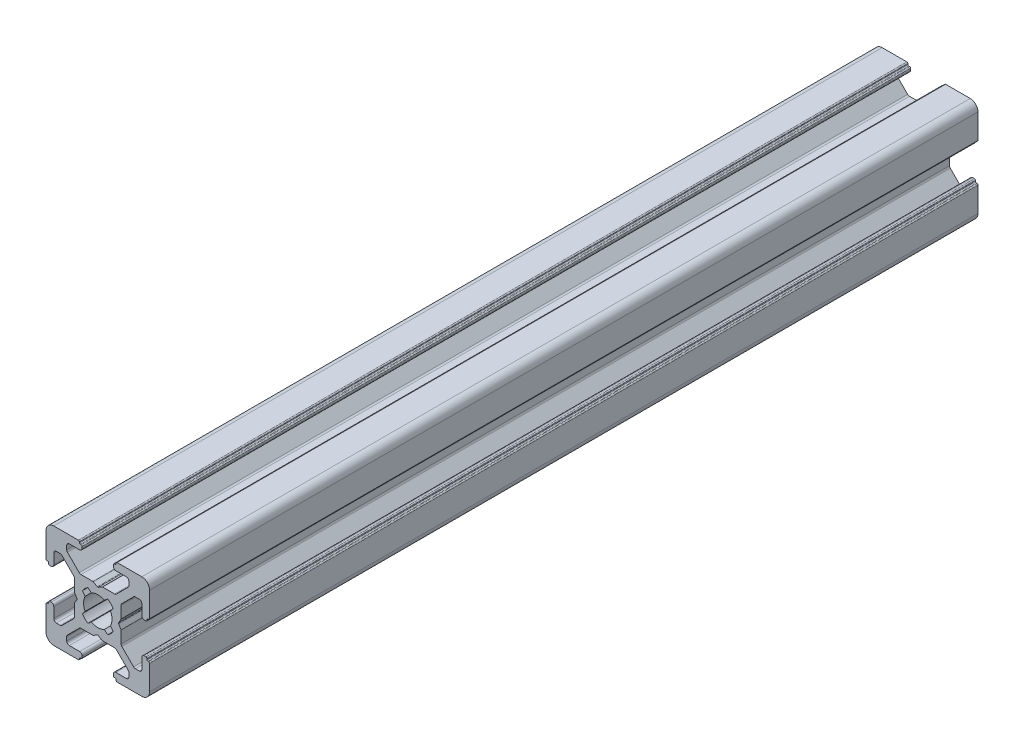
SolidWorks part; units mm, degrees
ref_plane "Front Plane" through (0, 0, 0) normal (0, 0, 1) x (1, 0, 0)
ref_plane "Top Plane" through (0, 0, 0) normal (0, 1, 0) x (1, 0, 0)
ref_plane "Right Plane" through (0, 0, 0) normal (1, 0, 0) x (0, 0, -1)
sketch "Sketch1" plane through (0, 0, 0) normal (0, 0, 1) x (1, 0, 0)
  line L0 (0, 13.3675) -> (0, -10.9159) construction
  line L1 (-12.9725, 0) -> (15.1887, 0) construction
  line L2 (-3.5, 8.5) -> (-5.5, 8.5)
  line L3 (-3.55, 9.7) -> (-3.55, 9.8)
  line L4 (-6, 7.2678) -> (-6, 8)
  line L5 (-7.2678, 6) -> (-8, 6)
  line L6 (-3.75, 10) -> (-8.5, 10)
  line L7 (-9.7, 3.55) -> (-9.8, 3.55)
  line L8 (-9.5, 3.2) -> (-9.5, 3.35)
  line L9 (-9, 3) -> (-9.3, 3)
  line L10 (-4.4732, 0.8536) -> (-4.0381, 0.1)
  line L11 (-4.5, 3.2322) -> (-4.5, 0.9536)
  line L12 (-8.5, 3.5) -> (-8.5, 5.5)
  line L13 (-10, 3.75) -> (-10, 8.5)
  line L14 (-3.5858, 4.6464) -> (-5.8536, 6.9142)
  line L15 (-4.6464, 3.5858) -> (-6.9142, 5.8536)
  line L16 (-3.2, 9.5) -> (-3.35, 9.5)
  line L17 (-3, 9) -> (-3, 9.3)
  line L18 (-0.8536, 4.4732) -> (-0.1, 4.0381)
  line L19 (-3.2322, 4.5) -> (-0.9536, 4.5)
  line L20 (-1.2582, 2.4453) -> (-1.9139, 2.9896)
  line L21 (-2.4453, 1.2582) -> (-2.9922, 1.9099)
  line L22 (3.5, -8.5) -> (5.5, -8.5)
  line L23 (3.55, -9.7) -> (3.55, -9.8)
  line L24 (6, -7.2678) -> (6, -8)
  line L25 (7.2678, -6) -> (8, -6)
  line L26 (3.75, -10) -> (8.5, -10)
  line L27 (9.7, -3.55) -> (9.8, -3.55)
  line L28 (9.5, -3.2) -> (9.5, -3.35)
  line L29 (9, -3) -> (9.3, -3)
  line L30 (4.4732, -0.8536) -> (4.0381, -0.1)
  line L31 (4.5, -3.2322) -> (4.5, -0.9536)
  line L32 (8.5, -3.5) -> (8.5, -5.5)
  line L33 (10, -3.75) -> (10, -8.5)
  line L34 (3.5858, -4.6464) -> (5.8536, -6.9142)
  line L35 (4.6464, -3.5858) -> (6.9142, -5.8536)
  line L36 (3.2, -9.5) -> (3.35, -9.5)
  line L37 (3, -9) -> (3, -9.3)
  line L38 (0.8536, -4.4732) -> (0.1, -4.0381)
  line L39 (3.2322, -4.5) -> (0.9536, -4.5)
  line L40 (1.2582, -2.4453) -> (1.9139, -2.9896)
  line L41 (2.4453, -1.2582) -> (2.9922, -1.9099)
  line L42 (-2.4453, -1.2582) -> (-2.9922, -1.9099)
  line L43 (-1.2582, -2.4453) -> (-1.9139, -2.9896)
  line L44 (-3.2322, -4.5) -> (-0.9536, -4.5)
  line L45 (-0.8536, -4.4732) -> (-0.1, -4.0381)
  line L46 (-3, -9) -> (-3, -9.3)
  line L47 (-3.2, -9.5) -> (-3.35, -9.5)
  line L48 (-4.6464, -3.5858) -> (-6.9142, -5.8536)
  line L49 (-3.5858, -4.6464) -> (-5.8536, -6.9142)
  line L50 (-10, -3.75) -> (-10, -8.5)
  line L51 (-8.5, -3.5) -> (-8.5, -5.5)
  line L52 (-4.5, -3.2322) -> (-4.5, -0.9536)
  line L53 (-4.4732, -0.8536) -> (-4.0381, -0.1)
  line L54 (-9, -3) -> (-9.3, -3)
  line L55 (-9.5, -3.2) -> (-9.5, -3.35)
  line L56 (-9.7, -3.55) -> (-9.8, -3.55)
  line L57 (2.4453, 1.2582) -> (2.9922, 1.9099)
  line L58 (1.2582, 2.4453) -> (1.9139, 2.9896)
  line L59 (3.2322, 4.5) -> (0.9536, 4.5)
  line L60 (0.8536, 4.4732) -> (0.1, 4.0381)
  line L61 (-3.75, -10) -> (-8.5, -10)
  line L62 (-7.2678, -6) -> (-8, -6)
  line L63 (-6, -7.2678) -> (-6, -8)
  line L64 (3, 9) -> (3, 9.3)
  line L65 (3.2, 9.5) -> (3.35, 9.5)
  line L66 (4.6464, 3.5858) -> (6.9142, 5.8536)
  line L67 (3.5858, 4.6464) -> (5.8536, 6.9142)
  line L68 (10, 3.75) -> (10, 8.5)
  line L69 (8.5, 3.5) -> (8.5, 5.5)
  line L70 (4.5, 3.2322) -> (4.5, 0.9536)
  line L71 (4.4732, 0.8536) -> (4.0381, 0.1)
  line L72 (9, 3) -> (9.3, 3)
  line L73 (9.5, 3.2) -> (9.5, 3.35)
  line L74 (9.7, 3.55) -> (9.8, 3.55)
  line L75 (3.75, 10) -> (8.5, 10)
  line L76 (7.2678, 6) -> (8, 6)
  line L77 (6, 7.2678) -> (6, 8)
  line L78 (3.55, 9.7) -> (3.55, 9.8)
  line L79 (3.5, 8.5) -> (5.5, 8.5)
  line L80 (-3.55, -9.7) -> (-3.55, -9.8)
  line L81 (-3.5, -8.5) -> (-5.5, -8.5)
  arc A0 (-10, 8.5) -> (-8.5, 10) centre (-8.5, 8.5) cw
  arc A1 (-8.5, 5.5) -> (-8, 6) centre (-8, 5.5) cw
  arc A2 (-7.2678, 6) -> (-6.9142, 5.8536) centre (-7.2678, 5.5) cw
  arc A3 (-5.8536, 6.9142) -> (-6, 7.2678) centre (-5.5, 7.2678) cw
  arc A4 (-6, 8) -> (-5.5, 8.5) centre (-5.5, 8) cw
  arc A5 (-9.7, 3.55) -> (-9.5, 3.35) centre (-9.7, 3.35) cw
  arc A6 (-9.8, 3.55) -> (-10, 3.75) centre (-9.8, 3.75) cw
  arc A7 (-9.3, 3) -> (-9.5, 3.2) centre (-9.3, 3.2) cw
  arc A8 (-8.5, 3.5) -> (-9, 3) centre (-9, 3.5) cw
  arc A9 (-4.6464, 3.5858) -> (-4.5, 3.2322) centre (-5, 3.2322) cw
  arc A10 (-4.4732, 0.8536) -> (-4.5, 0.9536) centre (-4.3, 0.9536) cw
  arc A11 (-4.0381, 0.1) -> (-4.0381, -0.1) centre (-4.2113, 0) cw
  arc A12 (-3.2, 9.5) -> (-3, 9.3) centre (-3.2, 9.3) cw
  arc A13 (-0.9536, 4.5) -> (-0.8536, 4.4732) centre (-0.9536, 4.3) cw
  arc A14 (-2.9922, 1.9099) -> (-1.9139, 2.9896) centre (0, 0) cw
  arc A15 (-3.2322, 4.5) -> (-3.5858, 4.6464) centre (-3.2322, 5) cw
  arc A16 (-3.75, 10) -> (-3.55, 9.8) centre (-3.75, 9.8) cw
  arc A17 (-3.35, 9.5) -> (-3.55, 9.7) centre (-3.35, 9.7) cw
  arc A18 (2.4453, -1.2582) -> (2.4453, 1.2582) centre (0, 0) ccw
  arc A19 (-3, 9) -> (-3.5, 8.5) centre (-3.5, 9) cw
  arc A20 (-2.4453, -1.2582) -> (-2.4453, 1.2582) centre (0, 0) cw
  arc A21 (10, -8.5) -> (8.5, -10) centre (8.5, -8.5) cw
  arc A22 (8.5, -5.5) -> (8, -6) centre (8, -5.5) cw
  arc A23 (7.2678, -6) -> (6.9142, -5.8536) centre (7.2678, -5.5) cw
  arc A24 (5.8536, -6.9142) -> (6, -7.2678) centre (5.5, -7.2678) cw
  arc A25 (6, -8) -> (5.5, -8.5) centre (5.5, -8) cw
  arc A26 (9.7, -3.55) -> (9.5, -3.35) centre (9.7, -3.35) cw
  arc A27 (9.8, -3.55) -> (10, -3.75) centre (9.8, -3.75) cw
  arc A28 (9.3, -3) -> (9.5, -3.2) centre (9.3, -3.2) cw
  arc A29 (8.5, -3.5) -> (9, -3) centre (9, -3.5) cw
  arc A30 (4.6464, -3.5858) -> (4.5, -3.2322) centre (5, -3.2322) cw
  arc A31 (4.4732, -0.8536) -> (4.5, -0.9536) centre (4.3, -0.9536) cw
  arc A32 (3.2, -9.5) -> (3, -9.3) centre (3.2, -9.3) cw
  arc A33 (-0.1, -4.0381) -> (0.1, -4.0381) centre (0, -4.2113) cw
  arc A34 (0.9536, -4.5) -> (0.8536, -4.4732) centre (0.9536, -4.3) cw
  arc A35 (2.9922, -1.9099) -> (1.9139, -2.9896) centre (0, 0) cw
  arc A36 (1.2582, -2.4453) -> (-1.2582, -2.4453) centre (0, 0) cw
  arc A37 (3.2322, -4.5) -> (3.5858, -4.6464) centre (3.2322, -5) cw
  arc A38 (3.75, -10) -> (3.55, -9.8) centre (3.75, -9.8) cw
  arc A39 (3.35, -9.5) -> (3.55, -9.7) centre (3.35, -9.7) cw
  arc A40 (3, -9) -> (3.5, -8.5) centre (3.5, -9) cw
  arc A41 (-3, -9) -> (-3.5, -8.5) centre (-3.5, -9) ccw
  arc A42 (-3.35, -9.5) -> (-3.55, -9.7) centre (-3.35, -9.7) ccw
  arc A43 (-3.75, -10) -> (-3.55, -9.8) centre (-3.75, -9.8) ccw
  arc A44 (-3.2322, -4.5) -> (-3.5858, -4.6464) centre (-3.2322, -5) ccw
  arc A45 (-2.9922, -1.9099) -> (-1.9139, -2.9896) centre (0, 0) ccw
  arc A46 (-0.9536, -4.5) -> (-0.8536, -4.4732) centre (-0.9536, -4.3) ccw
  arc A47 (-3.2, -9.5) -> (-3, -9.3) centre (-3.2, -9.3) ccw
  arc A48 (-4.4732, -0.8536) -> (-4.5, -0.9536) centre (-4.3, -0.9536) ccw
  arc A49 (3, 9) -> (3.5, 8.5) centre (3.5, 9) ccw
  arc A50 (3.35, 9.5) -> (3.55, 9.7) centre (3.35, 9.7) ccw
  arc A51 (3.75, 10) -> (3.55, 9.8) centre (3.75, 9.8) ccw
  arc A52 (3.2322, 4.5) -> (3.5858, 4.6464) centre (3.2322, 5) ccw
  arc A53 (1.2582, 2.4453) -> (-1.2582, 2.4453) centre (0, 0) ccw
  arc A54 (-4.6464, -3.5858) -> (-4.5, -3.2322) centre (-5, -3.2322) ccw
  arc A55 (-8.5, -3.5) -> (-9, -3) centre (-9, -3.5) ccw
  arc A56 (-9.3, -3) -> (-9.5, -3.2) centre (-9.3, -3.2) ccw
  arc A57 (-9.8, -3.55) -> (-10, -3.75) centre (-9.8, -3.75) ccw
  arc A58 (-9.7, -3.55) -> (-9.5, -3.35) centre (-9.7, -3.35) ccw
  arc A59 (-6, -8) -> (-5.5, -8.5) centre (-5.5, -8) ccw
  arc A60 (2.9922, 1.9099) -> (1.9139, 2.9896) centre (0, 0) ccw
  arc A61 (0.9536, 4.5) -> (0.8536, 4.4732) centre (0.9536, 4.3) ccw
  arc A62 (-0.1, 4.0381) -> (0.1, 4.0381) centre (0, 4.2113) ccw
  arc A63 (-5.8536, -6.9142) -> (-6, -7.2678) centre (-5.5, -7.2678) ccw
  arc A64 (-7.2678, -6) -> (-6.9142, -5.8536) centre (-7.2678, -5.5) ccw
  arc A65 (-8.5, -5.5) -> (-8, -6) centre (-8, -5.5) ccw
  arc A66 (-10, -8.5) -> (-8.5, -10) centre (-8.5, -8.5) ccw
  arc A67 (3.2, 9.5) -> (3, 9.3) centre (3.2, 9.3) ccw
  arc A68 (4.0381, 0.1) -> (4.0381, -0.1) centre (4.2113, 0) ccw
  arc A69 (4.4732, 0.8536) -> (4.5, 0.9536) centre (4.3, 0.9536) ccw
  arc A70 (4.6464, 3.5858) -> (4.5, 3.2322) centre (5, 3.2322) ccw
  arc A71 (8.5, 3.5) -> (9, 3) centre (9, 3.5) ccw
  arc A72 (9.3, 3) -> (9.5, 3.2) centre (9.3, 3.2) ccw
  arc A73 (9.8, 3.55) -> (10, 3.75) centre (9.8, 3.75) ccw
  arc A74 (9.7, 3.55) -> (9.5, 3.35) centre (9.7, 3.35) ccw
  arc A75 (6, 8) -> (5.5, 8.5) centre (5.5, 8) ccw
  arc A76 (5.8536, 6.9142) -> (6, 7.2678) centre (5.5, 7.2678) ccw
  arc A77 (7.2678, 6) -> (6.9142, 5.8536) centre (7.2678, 5.5) ccw
  arc A78 (8.5, 5.5) -> (8, 6) centre (8, 5.5) ccw
  arc A79 (10, 8.5) -> (8.5, 10) centre (8.5, 8.5) ccw
  dimension "D4" = 5.5
  dimension "D1" = 6
  dimension "D2" = 20
  dimension "D3" = 20
  dimension "D5" = 5.5
  dimension "D6" = 10
  dimension "D7" = 6
  dimension "D8" = 6
  dimension "D9" = 6
extrude "Extrude1" add sketch "Sketch1" along normal blind 160
